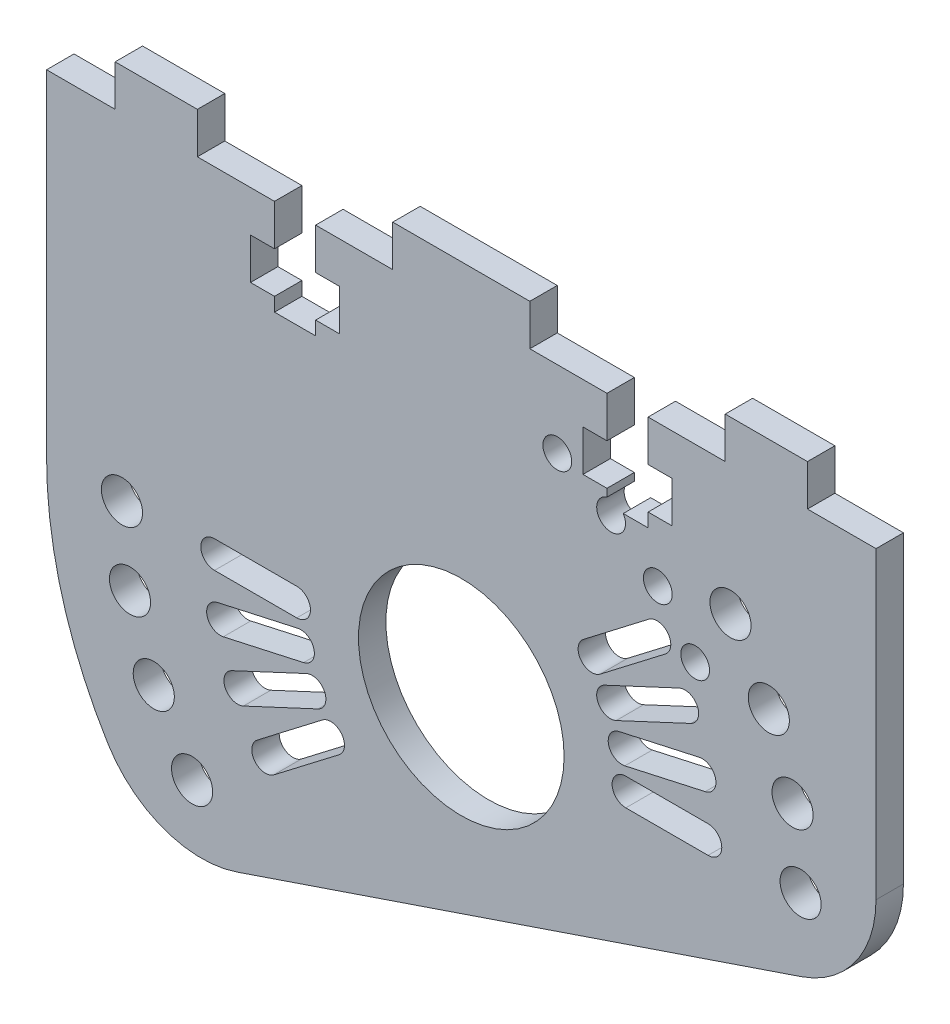
SolidWorks part; units mm, degrees
material "Thornel Mat VMA"
ref_plane "前视基准面" through (0, 0, 0) normal (0, 0, 1) x (1, 0, 0)
ref_plane "上视基准面" through (0, 0, 0) normal (0, 1, 0) x (1, 0, 0)
ref_plane "右视基准面" through (0, 0, 0) normal (1, 0, 0) x (0, 0, -1)
sketch "草图1" plane through (0, 0, 0) normal (0, 0, 1) x (1, 0, 0)
  line L0 (0, 16.0845) -> (0, -17.1239) construction
  line L1 (-20.1071, 0) -> (25.3101, 0) construction
  line L7 (12, 1) -> (18, 1) construction
  line L8 (12, 1) -> (12, -1) construction
  line L9 (12, -1) -> (18, -1) construction
  line L10 (18, 1) -> (18, -1) construction
  line L18 (0, -24.75) -> (0, 24.75) construction
  line L23 (-12, -1) -> (-12, 1) construction
  line L24 (-12, -1) -> (-18, -1) construction
  line L25 (-18, -1) -> (-18, 1) construction
  line L26 (-12, 1) -> (-18, 1) construction
  line L39 (-1, 12) -> (1, 12) [skipped]
  line L40 (1, 12) -> (1, 18) [skipped]
  line L41 (-1, 18) -> (1, 18) [skipped]
  line L42 (-1, 12) -> (-1, 18) [skipped]
  line L43 (1, -12) -> (-1, -12) [skipped]
  line L44 (-1, -12) -> (-1, -18) [skipped]
  line L45 (1, -18) -> (-1, -18) [skipped]
  line L46 (1, -12) -> (1, -18) [skipped]
  line L60 (-30.75, 27.5) -> (30.75, 27.5)
  line L61 (-30.75, 27.5) -> (-30.75, -27.5)
  line L62 (-30.75, -27.5) -> (30.75, -27.5)
  line L63 (30.75, 27.5) -> (30.75, -27.5)
  line L64 (-30.75, 27.5) -> (30.75, -27.5) construction
  line L65 (-30.75, -27.5) -> (30.75, 27.5) construction
  circle A0 centre (-24.75, 0) radius 1.5 construction
  circle A5 centre (24.75, 0) radius 1.5 construction
  circle A8 centre (0, 24.75) radius 1.5 [skipped]
  circle A9 centre (0, 0) radius 51.2633 construction
  circle A10 centre (0, -24.75) radius 1.5 [skipped]
  circle A11 centre (0, 0) radius 7.5
  point P7 (0, 0)
  point P11 (-15, 1)
  point P19 (15, 1)
  point P34 (0, 0)
  dimension "D1" = 2
  dimension "D4" = 49.5
  dimension "D5" = 3
  dimension "D9" = 15
  dimension "D2" = 6
  dimension "D3" = 30
  dimension "D7" = 55
  dimension "D8" = 61.5
  dimension "D6" = 4
extrude "凸台-拉伸1" add sketch "草图1" along normal blind 2
sketch "草图2" plane through (0, 0, 2) normal (0, 0, 1) x (1, 0, 0)
  line L0 (24.75, 0) -> (12, 0) construction
  line L1 (-18, 1) -> (-12, 1)
  line L3 (-18, -1) -> (-12, -1)
  line L5 (12, 1) -> (18, 1)
  line L7 (12, -1) -> (18, -1)
  line L9 (17.06, -1) -> (17.06, 10.73) construction
  circle A0 centre (24.75, 0) radius 1.5 construction
  circle A1 centre (-24.75, 0) radius 1.5 construction
  circle A2 centre (24.75, 0) radius 1.5
  circle A3 centre (-24.75, 0) radius 1.5
  arc A4 (-18, 1) -> (-18, -1) centre (-18, 0) ccw
  arc A5 (-12, -1) -> (-12, 1) centre (-12, 0) ccw
  arc A6 (18, -1) -> (18, 1) centre (18, 0) ccw
  arc A7 (12, 1) -> (12, -1) centre (12, 0) ccw
  circle A8 centre (17.06, 10.73) radius 1.05
  dimension "D1" = 11.73
  dimension "D3" = 2.1
  dimension "D2" = 0.94
extrude "切除-拉伸1" cut sketch "草图2" against normal through all
pattern_circular "阵列(圆周)1" count 4 every 12.5 about axis through (0, 0, 0) along (0, 0, 1) of "切除-拉伸1"
sketch "草图3" plane through (0, 0, 2) normal (0, 0, 1) x (1, 0, 0)
  line L2 (-19.6355, -15.0668) -> (24.75, 0) construction
  line L3 (-21.7201, -21.0547) -> (30.049, -3.4815)
  line L4 (-30.75, 27.5) -> (-30.75, -27.5) construction
  line L5 (0, 0) -> (-30.75, 0) construction
  line L7 (-30.75, 0) -> (-30.75, -27.5)
  line L8 (-30.75, -27.5) -> (30.75, -27.5)
  line L9 (30.75, -27.5) -> (30.75, 0)
  line L10 (30.75, -27.5) -> (30.75, 27.5) construction
  line L12 (-30.75, 0) -> (-30.75, 27.5)
  line L13 (-30.75, 27.5) -> (-30.25, 27.5)
  line L14 (30.75, 27.5) -> (-30.75, 27.5) construction
  line L15 (-30.25, 27.5) -> (-30.25, 0)
  line L16 (30.25, 0) -> (30.25, 27.5)
  line L17 (30.25, 27.5) -> (30.75, 27.5)
  line L18 (30.75, 27.5) -> (30.75, 0)
  arc A0 (30.049, -3.4815) -> (30.25, 0) centre (0, 0) ccw
  circle A1 centre (-19.6355, -15.0668) radius 1.5 construction
  arc A2 (-30.25, 0) -> (-21.7201, -21.0547) centre (0, 0) ccw
  dimension "D1" = 5
  dimension "D2" = 0.5
extrude "切除-拉伸2" cut sketch "草图3" against normal through all
fillet "圆角1" radius 8 2 edges at (30.049, -3.4815, 1) (-21.7201, -21.0547, 1)
sketch "草图5" plane through (0, 0, 2) normal (0, 0, 1) x (1, 0, 0)
  line L0 (0, 41.3969) -> (0, 0) construction
  line L1 (30.25, 27.5) -> (-30.25, 27.5) construction
  line L2 (-30.25, 27.5) -> (-25.25, 27.5)
  line L3 (-30.25, 27.5) -> (-30.25, 24.5)
  line L4 (-30.25, 24.5) -> (-25.25, 24.5)
  line L5 (-25.25, 27.5) -> (-25.25, 24.5)
  line L6 (-30.25, 0) -> (-30.25, 27.5) construction
  line L7 (30.25, 27.5) -> (30.25, 2.3195) construction
  line L8 (-19.25, 27.5) -> (-5, 27.5)
  line L9 (-19.25, 27.5) -> (-19.25, 24.5)
  line L10 (-19.25, 24.5) -> (-5, 24.5) construction
  line L11 (-5, 27.5) -> (-5, 24.5)
  line L16 (5, 27.5) -> (19.25, 27.5)
  line L17 (5, 27.5) -> (5, 24.5)
  line L18 (5, 24.5) -> (19.25, 24.5) construction
  line L19 (19.25, 27.5) -> (19.25, 24.5)
  line L20 (25.25, 27.5) -> (30.25, 27.5)
  line L21 (25.25, 27.5) -> (25.25, 24.5)
  line L22 (25.25, 24.5) -> (30.25, 24.5)
  line L23 (30.25, 27.5) -> (30.25, 24.5)
  line L24 (-12.125, 27.5) -> (-12.125, 14.3705) construction
  line L25 (-10.625, 21.5) -> (-8.875, 21.5)
  line L26 (-13.625, 24.5) -> (-10.625, 24.5) construction
  line L27 (-13.625, 24.5) -> (-13.625, 21.5)
  line L28 (-13.625, 17.5) -> (-10.625, 17.5)
  line L29 (-10.625, 24.5) -> (-10.625, 21.5)
  line L30 (-15.375, 21.5) -> (-13.625, 21.5)
  line L31 (-15.375, 21.5) -> (-15.375, 18.5)
  line L32 (-15.375, 18.5) -> (-13.625, 18.5)
  line L33 (-8.875, 21.5) -> (-8.875, 18.5)
  line L34 (-13.625, 18.5) -> (-13.625, 17.5)
  line L35 (-10.625, 18.5) -> (-10.625, 17.5)
  line L36 (-10.625, 18.5) -> (-8.875, 18.5)
  line L37 (15.375, 21.5) -> (13.625, 21.5)
  line L38 (13.625, 24.5) -> (13.625, 21.5)
  line L39 (13.625, 24.5) -> (10.625, 24.5) construction
  line L40 (10.625, 24.5) -> (10.625, 21.5)
  line L41 (10.625, 21.5) -> (8.875, 21.5)
  line L42 (8.875, 21.5) -> (8.875, 18.5)
  line L43 (10.625, 18.5) -> (8.875, 18.5)
  line L44 (10.625, 18.5) -> (10.625, 17.5)
  line L45 (13.625, 17.5) -> (10.625, 17.5)
  line L46 (13.625, 18.5) -> (13.625, 17.5)
  line L47 (15.375, 18.5) -> (13.625, 18.5)
  line L48 (15.375, 21.5) -> (15.375, 18.5)
  line L49 (-19.25, 24.5) -> (-13.625, 24.5)
  line L50 (-10.625, 24.5) -> (-5, 24.5)
  line L51 (5, 24.5) -> (10.625, 24.5)
  line L52 (13.625, 24.5) -> (19.25, 24.5)
  dimension "D1" = 10
  dimension "D2" = 6
  dimension "D3" = 5
  dimension "D4" = 3
  dimension "D5" = 10
  dimension "D6" = 3
  dimension "D7" = 3
  dimension "D8" = 6.5
  dimension "D9" = 6
extrude "切除-拉伸3" cut sketch "草图5" against normal through all
